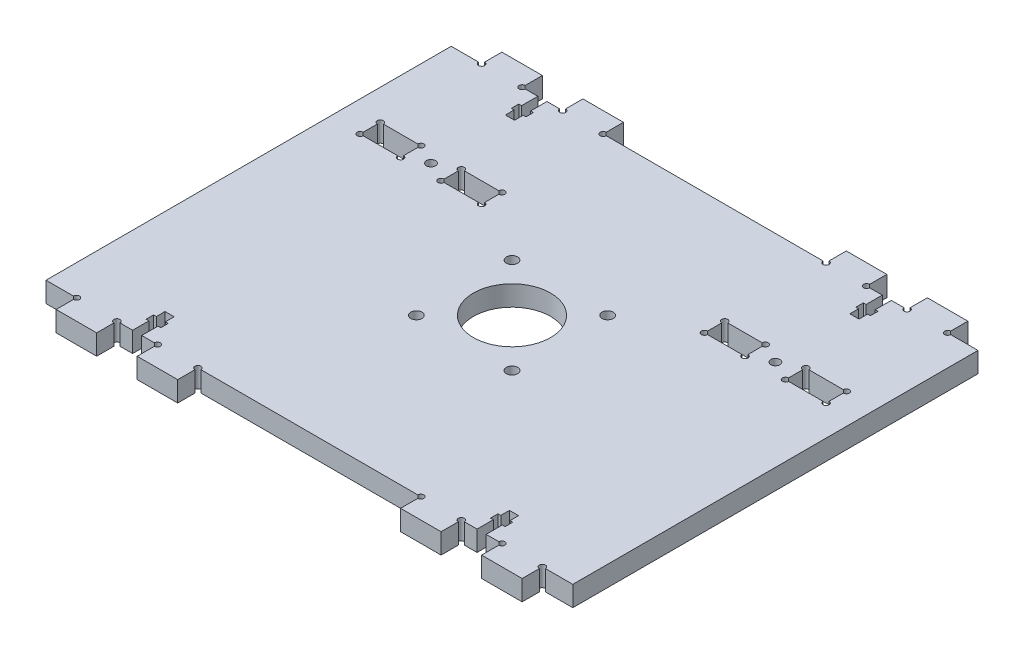
SolidWorks part; units mm, degrees
material "POLICARB. TRANSP."
ref_plane "Front Plane" through (0, 0, 0) normal (0, 0, 1) x (1, 0, 0)
ref_plane "Top Plane" through (0, 0, 0) normal (0, 1, 0) x (1, 0, 0)
ref_plane "Right Plane" through (0, 0, 0) normal (1, 0, 0) x (0, 0, -1)
sketch "Sketch1" plane through (0, 0, 0) normal (0, 1, 0) x (1, 0, 0)
  line L1 (130, 100) -> (-130, 100)
  line L2 (130, 100) -> (130, -100)
  line L3 (130, -100) -> (-130, -100)
  line L4 (-130, 100) -> (-130, -100)
  line L5 (0, -100) -> (0, 100) construction
  line L6 (130, 0) -> (-130, 0) construction
  point P0 (0, 0)
  dimension "D1" = 200
  dimension "D2" = 260
extrude "Extrude1" add sketch "Sketch1" along normal blind 10
sketch "Sketch3" plane through (0, 10, 0) normal (0, 1, 0) x (1, 0, 0)
  line L0 (130, 100) -> (-130, 100) construction
  line L1 (-115, 50) -> (-95, 50)
  line L2 (-115, 50) -> (-115, 40)
  line L3 (-115, 40) -> (-95, 40)
  line L4 (-95, 50) -> (-95, 40)
  line L9 (95, 50) -> (115, 50)
  line L10 (95, 50) -> (95, 40)
  line L11 (95, 40) -> (115, 40)
  line L12 (115, 50) -> (115, 40)
  line L13 (0, 0) -> (0, -100) construction
  line L14 (-130, -100) -> (130, -100) construction
  line L15 (-130, 100) -> (-130, -100) construction
  line L17 (-75, 50) -> (-55, 50)
  line L18 (-75, 50) -> (-75, 40)
  line L19 (-75, 40) -> (-55, 40)
  line L20 (-55, 50) -> (-55, 40)
  line L21 (55, 50) -> (75, 50)
  line L22 (55, 50) -> (55, 40)
  line L23 (55, 40) -> (75, 40)
  line L24 (75, 50) -> (75, 40)
  dimension "D1" = 50
  dimension "D2" = 20
  dimension "D3" = 10
  dimension "D4" = 15
  dimension "D5" = 20
  dimension "D6" = 10
  dimension "D7" = 20
extrude "Extrude2" cut sketch "Sketch3" against normal blind 10
hole_wizard "M4 Clearance Hole1" positions "Sketch4" profile "Sketch5" hole size "M4" standard "DIN" end condition through all
sketch "Sketch4" plane through (0, 10, 0) normal (0, 1, 0) x (1, 0, 0)
  line L0 (0, 0) -> (0, 100) construction
  line L8 (130, 100) -> (-130, 100) construction
  line L9 (-95, 45) -> (-75, 45) construction
  line L10 (-95, 40) -> (-95, 50) construction
  line L11 (-75, 50) -> (-75, 40) construction
  line L13 (-85, 45) -> (-85, 100) construction
  point P0 (-85, 45)
  point P2 (85, 45)
sketch "Sketch5" plane through (-85, 10, -45) normal (1, 0, 0) x (0, 0, 1)
  line L0 (0, 0) -> (0, 10)
  line L1 (0, 10) -> (2.25, 10)
  line L2 (2.25, 10) -> (2.25, 0)
  line L5 (2.25, 0) -> (0, 0)
  line L11 (0, -6.35) -> (0, 107.95) construction
  dimension "Thru Hole Dia." = 4.5
  dimension "Thru Hole Depth" = 10
sketch "Sketch6" plane through (0, 10, 0) normal (0, 1, 0) x (1, 0, 0)
  line L0 (-113.5, 50) -> (-115, 50)
  line L1 (-115, 50) -> (-115, 48.5)
  line L2 (-113.5, 40) -> (-115, 40)
  line L3 (-115, 40) -> (-115, 41.5)
  arc A0 (-115, 41.5) -> (-113.5, 40) centre (-115, 40) ccw
  arc A1 (-113.5, 50) -> (-115, 48.5) centre (-115, 50) ccw
  dimension "D1" = 3
extrude "Extrude3" cut sketch "Sketch6" against normal blind 10
ref_plane "Plane1" through (-105, 0, 0) normal (1, 0, 0) x (0, 0, -1)
mirror "Mirror1" about plane through (-105, 0, 0) normal (1, 0, 0) of "Extrude3"
ref_plane "Plane2" through (-85, 0, 0) normal (-1, 0, 0) x (0, 0, 1)
mirror "Mirror2" about plane through (-85, 0, 0) normal (-1, 0, 0) of "Mirror1", "Extrude3"
ref_plane "Plane3" through (0, 0, 0) normal (1, 0, 0) x (0, 0, -1)
mirror "Mirror3" about plane through (0, 0, 0) normal (1, 0, 0) of "Mirror2", "Mirror1", "Extrude3"
sketch "Sketch7" plane through (0, 10, 0) normal (0, 1, 0) x (1, 0, 0)
  line L0 (-130, -100) -> (130, -100) construction
  line L1 (-115, -100) -> (-95, -100)
  line L2 (-115, -100) -> (-115, -110)
  line L3 (-115, -110) -> (-95, -110)
  line L4 (-95, -100) -> (-95, -110)
  line L5 (-130, 100) -> (-130, -100) construction
  line L6 (-75, -100) -> (-55, -100)
  line L7 (-75, -100) -> (-75, -110)
  line L8 (-75, -110) -> (-55, -110)
  line L9 (-55, -100) -> (-55, -110)
  dimension "D1" = 20
  dimension "D2" = 15
  dimension "D3" = 20
  dimension "D4" = 10
extrude "Extrude4" add sketch "Sketch7" against normal blind 10
pattern_linear "LPattern1" count 2 spacing 170 along (1, 0, 0) count 2 spacing 210 along (0, 0, -1) of "Extrude4"
sketch "Sketch8" plane through (0, 10, 0) normal (0, 1, 0) x (1, 0, 0)
  line L0 (-116.5, -100) -> (-115, -100)
  line L1 (-115, -100) -> (-115, -101.5)
  line L3 (-95, -101.5) -> (-95, -100)
  line L4 (-95, -100) -> (-93.5, -100)
  line L5 (-75, -100) -> (-75, -101.5)
  line L7 (-55, -101.5) -> (-55, -100)
  line L8 (-55, -100) -> (-53.5, -100)
  line L9 (-55, -110) -> (-55, -100) construction
  line L10 (-76.5, -100) -> (-75, -100)
  arc A0 (-115, -101.5) -> (-116.5, -100) centre (-115, -100) ccw
  arc A1 (-93.5, -100) -> (-95, -101.5) centre (-95, -100) ccw
  arc A2 (-75, -101.5) -> (-76.5, -100) centre (-75, -100) ccw
  arc A3 (-53.5, -100) -> (-55, -101.5) centre (-55, -100) ccw
  dimension "D1" = 3
extrude "Extrude5" cut sketch "Sketch8" against normal blind 10
ref_plane "Plane4" through (0, 0, 0) normal (1, 0, 0) x (0, 0, -1)
ref_plane "Plane5" through (0, 0, 0) normal (0, 0, 1) x (1, 0, 0)
mirror "Mirror4" about plane through (0, 0, 0) normal (1, 0, 0) of "Extrude5"
mirror "Mirror5" about plane through (0, 0, 0) normal (0, 0, 1) of "Extrude5", "Mirror4"
sketch "Sketch9" plane through (0, 10, 0) normal (0, 1, 0) x (1, 0, 0)
  line L0 (-95, -105.75) -> (-75, -105.75) construction
  line L1 (-95, -110) -> (-95, -101.5) construction
  line L2 (-75, -101.5) -> (-75, -110) construction
  line L3 (-87.25, -100) -> (-87.25, -92)
  line L4 (-93.5, -100) -> (-76.5, -100) construction
  line L5 (-87.25, -92) -> (-88.625, -92)
  line L6 (-88.625, -92) -> (-88.625, -88.3)
  line L7 (-88.625, -88.3) -> (-87.25, -88.3)
  line L8 (-87.25, -88.3) -> (-87.25, -84)
  line L9 (-87.25, -84) -> (-82.75, -84)
  line L10 (-82.75, -84) -> (-82.75, -88.3)
  line L11 (-82.75, -88.3) -> (-81.375, -88.3)
  line L12 (-81.375, -88.3) -> (-81.375, -92)
  line L13 (-81.375, -92) -> (-82.75, -92)
  line L14 (-82.75, -92) -> (-82.75, -100)
  line L15 (-85, -105.75) -> (-85, -100) construction
  line L16 (-87.25, -100) -> (-82.75, -100)
  dimension "D1" = 16
  dimension "D2" = 8
  dimension "D3" = 4.5
  dimension "D4" = 7.25
  dimension "D5" = 3.7
extrude "Extrude6" cut sketch "Sketch9" against normal blind 10
mirror "Mirror6" about plane through (0, 0, 0) normal (1, 0, 0) of "Extrude6"
mirror "Mirror7" about plane through (0, 0, 0) normal (0, 0, 1) of "Mirror6", "Extrude6"
extrude "Cut-Extrude2" cut sketch "Sketch11" against normal blind 10
sketch "Sketch11" plane through (-130, 0, 110) normal (0, -1, 0) x (0, 0, 1)
  line L1 (-110, 0) -> (-110, -260) construction
  line L2 (-210, 0) -> (-10, 0) construction
  line L3 (-10, -260) -> (-210, -260) construction
  line L5 (-10, -76.5) -> (-10, -183.5) construction
  line L6 (-10, -130) -> (-210, -130) construction
  line L7 (-210, -183.5) -> (-210, -76.5) construction
  circle A0 centre (-110, -130) radius 19.05
  circle A2 centre (-133.6, -106.4) radius 2.75
  circle A3 centre (-133.6, -153.6) radius 2.75
  circle A4 centre (-86.4, -153.6) radius 2.75
  circle A5 centre (-86.4, -106.4) radius 2.75
  point P22 (0, 0)
  point P23 (0, 0)
  point P24 (0, 0)
  point P25 (0, 0)
  dimension "D1" = 47.2
  dimension "D2" = 38.1
  dimension "D4" = 5.5
  dimension "D3" = 47.2
